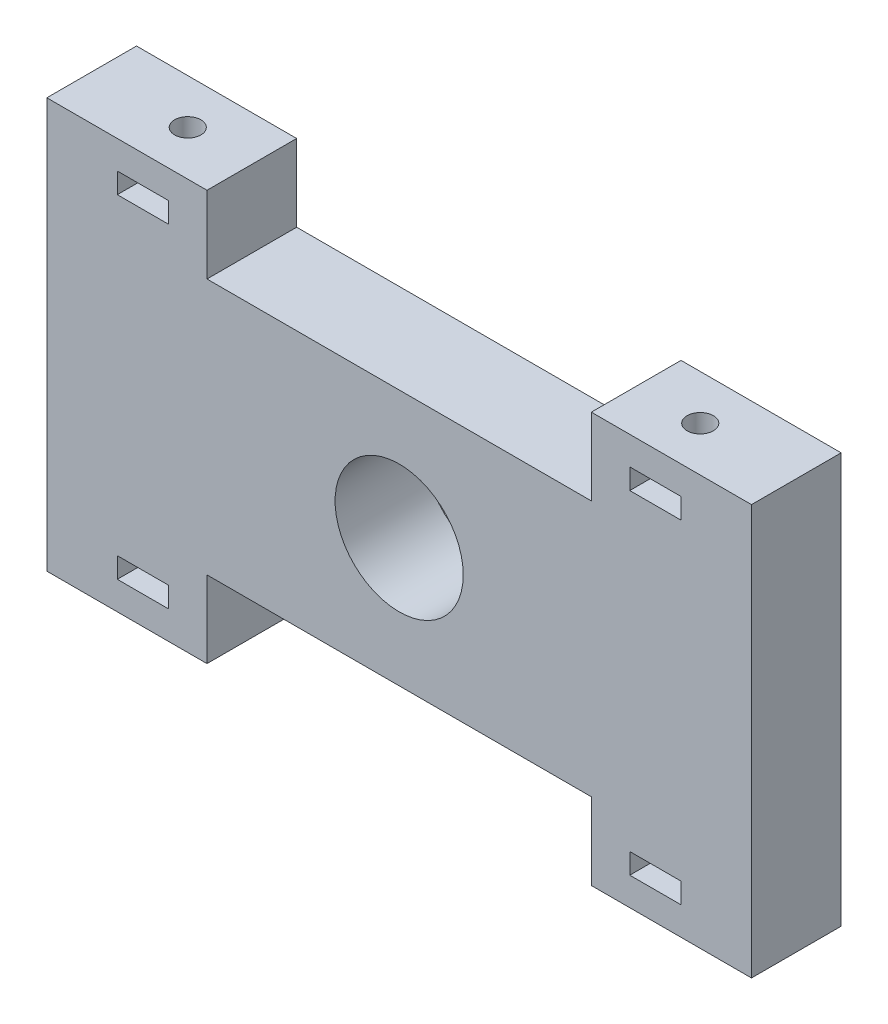
SolidWorks part; units mm, degrees
ref_plane "Front" through (0, 0, 0) normal (0, 0, 1) x (1, 0, 0)
ref_plane "Top" through (0, 0, 0) normal (0, 1, 0) x (1, 0, 0)
ref_plane "Right" through (0, 0, 0) normal (1, 0, 0) x (0, 0, -1)
sketch "草图1" plane through (0, 0, 0) normal (0, 0, 1) x (1, 0, 0)
  line L0 (-15, 10) -> (-15, 16)
  line L1 (27.5, -16) -> (15, -16)
  line L2 (27.5, -16) -> (27.5, 16)
  line L3 (27.5, 16) -> (15, 16)
  line L4 (-27.5, -16) -> (-27.5, 16)
  line L6 (15, 10) -> (15, 16)
  line L7 (-15, -10) -> (15, -10)
  line L8 (-15, 16) -> (-27.5, 16)
  line L9 (-15, 10) -> (15, 10)
  line L11 (-15, -10) -> (-15, -16)
  line L12 (15, -10) -> (15, -16)
  line L13 (-15, -16) -> (-27.5, -16)
  circle A0 centre (0, 0) radius 5
  point P0 (0, 0)
  point P6 (0, 0)
extrude "凸台-拉伸1" add sketch "草图1" along normal blind 7
sketch "草图2" plane through (0, 16, 0) normal (0, 1, 0) x (1, 0, 0)
  line L0 (-27.5, -3.5) -> (27.5, -3.5) construction
  line L1 (-27.5, -7) -> (-27.5, 0) construction
  line L2 (27.5, -7) -> (27.5, 0) construction
  line L3 (0, 0) -> (0, -7) construction
  line L4 (15, -7) -> (-15, -7) construction
  point P11 (-20, -3.5)
  point P12 (20, -3.5)
  dimension "D1" = 20
hole_wizard "M2.5x0.45 螺纹孔1" positions "3D草图1" profile "草图3" tap size "M2.5x0.45" standard "ANSI Metric" end condition through all
sketch3d "3D草图1"
  point P0 (-20, 16, 3.5)
  point P3 (20, 16, 3.5)
sketch "草图3" plane through (-20, 16, 3.5) normal (1, 0, 0) x (0, 0, 1)
  line L0 (0, 0) -> (0, 32)
  line L1 (0, 32) -> (1.025, 32)
  line L2 (1.025, 32) -> (1.025, 0)
  line L5 (1.025, 0) -> (0, 0)
  line L11 (0, -6.35) -> (0, 107.95) construction
  dimension "通孔螺纹孔钻头直径" = 2.05
  dimension "通孔螺纹孔钻头深度" = 32
cosmetic thread "孔螺蚊线1" parameters "D2"=2.5
cosmetic thread "孔螺蚊线2" parameters "D2"=2.5
ref_plane "基准面1" through (0, 13, 0) normal (0, 1, 0) x (1, 0, 0)
sketch "草图4" plane through (0, 13, 0) normal (0, 1, 0) x (1, 0, 0)
  line L0 (-22, -4.6547) -> (-22, -7)
  line L1 (20, -1.1906) -> (18, -2.3453)
  line L2 (18, -2.3453) -> (18, -4.6547)
  line L5 (22, -4.6547) -> (22, -2.3453)
  line L6 (22, -2.3453) -> (20, -1.1906)
  line L7 (-20, -1.1906) -> (-22, -2.3453)
  line L8 (-22, -2.3453) -> (-22, -4.6547)
  line L11 (-18, -4.6547) -> (-18, -2.3453)
  line L12 (-18, -2.3453) -> (-20, -1.1906)
  line L13 (-15, -7) -> (-27.5, -7) construction
  line L14 (-22, -7) -> (-18, -7)
  line L15 (-18, -7) -> (-18, -4.6547)
  line L16 (18, -4.6547) -> (18, -7)
  line L17 (27.5, -7) -> (15, -7) construction
  line L18 (18, -7) -> (22, -7)
  line L19 (22, -7) -> (22, -4.6547)
  line L21 (18, -4.6547) -> (20, -5.8094) [skipped]
  line L22 (20, -5.8094) -> (22, -4.6547) [skipped]
  line L23 (-20, -5.8094) -> (-18, -4.6547) [skipped]
  line L24 (-22, -4.6547) -> (-20, -5.8094) [skipped]
  circle A0 centre (20, -3.5) radius 2 construction
  circle A1 centre (-20, -3.5) radius 2 construction
extrude "切除-拉伸1" cut sketch "草图4" against normal mid plane 1.6
ref_plane "基准面2" through (0, -13, 0) normal (0, -1, 0) x (-1, 0, 0)
sketch "草图7" plane through (0, -13, 0) normal (0, -1, 0) x (-1, 0, 0)
  line L0 (-22, -4.6547) -> (-22, -7)
  line L1 (-20, -1.1906) -> (-22, -2.3453)
  line L2 (-22, -2.3453) -> (-22, -4.6547)
  line L5 (-18, -4.6547) -> (-18, -2.3453)
  line L6 (-18, -2.3453) -> (-20, -1.1906)
  line L7 (20, -1.1906) -> (18, -2.3453)
  line L8 (18, -2.3453) -> (18, -4.6547)
  line L11 (22, -4.6547) -> (22, -2.3453)
  line L12 (22, -2.3453) -> (20, -1.1906)
  line L13 (-15, -7) -> (-27.5, -7) construction
  line L14 (-22, -7) -> (-18, -7)
  line L15 (-18, -7) -> (-18, -4.6547)
  line L16 (18, -4.6547) -> (18, -7)
  line L17 (27.5, -7) -> (15, -7) construction
  line L18 (18, -7) -> (22, -7)
  line L19 (22, -7) -> (22, -4.6547)
  line L21 (20, -5.8094) -> (22, -4.6547) [skipped]
  line L22 (18, -4.6547) -> (20, -5.8094) [skipped]
  line L23 (-20, -5.8094) -> (-18, -4.6547) [skipped]
  line L24 (-22, -4.6547) -> (-20, -5.8094) [skipped]
  circle A0 centre (-20, -3.5) radius 2 construction
  circle A1 centre (20, -3.5) radius 2 construction
extrude "切除-拉伸3" cut sketch "草图7" against normal mid plane 1.6
